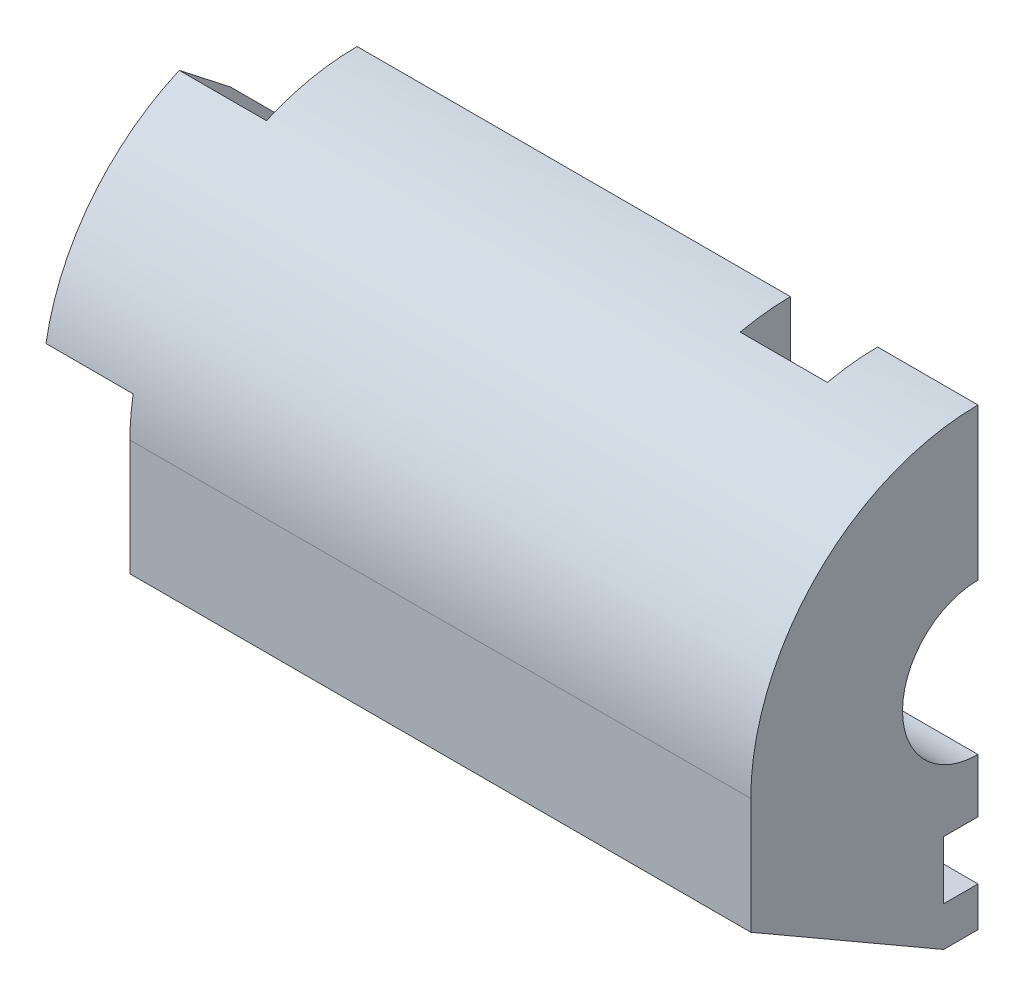
SolidWorks part; units mm, degrees
material "Alliage 1060"
ref_plane "Plan de face" through (0, 0, 0) normal (0, 0, 1) x (1, 0, 0)
ref_plane "Plan de dessus" through (0, 0, 0) normal (0, 1, 0) x (1, 0, 0)
ref_plane "Plan de droite" through (0, 0, 0) normal (1, 0, 0) x (0, 0, -1)
sketch "Esquisse1" plane through (0, 0, 0) normal (1, 0, 0) x (0, 0, -1)
  line L0 (0, 0) -> (0, 86)
  line L1 (0, 55) -> (0, -55) construction
  line L5 (-13, -86) -> (0, -86)
  line L6 (0, -86) -> (0, 0)
  line L7 (-13, -86) -> (-86, -43.8534)
  line L8 (-86, -43.8534) -> (-86, 0)
  arc A0 (0, 86) -> (-86, 0) centre (0, 0) ccw
  dimension "D1" = 86
  dimension "D2" = 86
  dimension "D3" = 13
  dimension "D4" = 86
extrude "Boss.-Extru.1" add sketch "Esquisse1" along normal blind 235 contours L8 A0 L0 L6 L5 L7
sketch "Esquisse2" plane through (0, 0, 0) normal (1, 0, 0) x (0, 0, -1)
  circle A0 centre (0, 0) radius 28.575
extrude "Enlèv. mat.-Extru.1" cut sketch "Esquisse2" along normal blind 235
sketch "Esquisse3" plane through (0, 0, 0) normal (1, 0, 0) x (0, 0, -1)
  circle A0 centre (0, 0) radius 44.45
extrude "Enlèv. mat.-Extru.2" cut sketch "Esquisse3" along normal blind 78
sketch "Esquisse4" plane through (0, 0, 0) normal (0, 0, 1) x (1, 0, 0)
  line L0 (235, 86) -> (197, 86)
  line L2 (235, 86) -> (0, 86) construction
  line L3 (197, 86) -> (197, 24.3686)
  line L4 (197, 86) -> (164, 86)
  line L5 (164, 86) -> (164, 24.3686)
  line L6 (197, 24.3686) -> (164, 24.3686)
  dimension "D1" = 38
  dimension "D2" = 33
extrude "Enlèv. mat.-Extru.3" cut sketch "Esquisse4" along normal blind 19 contours L6 L3 L4 L5
sketch "Esquisse5" plane through (0, 0, 0) normal (0, 0, 1) x (1, 0, 0)
  line L0 (235, -86) -> (235, -71)
  line L1 (235, -86) -> (235, -28.575) construction
  line L2 (235, -71) -> (125, -71)
  line L3 (235, -49) -> (235, -71)
  line L4 (125, -49) -> (235, -49)
  arc A0 (125, -71) -> (125, -49) centre (125, -60) cw
  dimension "D1" = 15
  dimension "D2" = 110
  dimension "D4" = 22
extrude "Enlèv. mat.-Extru.4" cut sketch "Esquisse5" along normal blind 13 contours A0 L2 L3 L4
sketch "Esquisse6" plane through (0, 0, 0) normal (1, 0, 0) x (0, 0, -1)
  line L0 (0, 0) -> (-40.1885, 31.3987)
  line L1 (47.3, 0) -> (-47.3, 0) construction
  line L2 (-40.1885, 31.3987) -> (-65.4307, -0.9097)
  line L3 (-14.9464, 63.7072) -> (-40.1885, 31.3987)
  line L4 (-14.9464, 63.7072) -> (-34.3296, 78.851)
  line L5 (-65.4307, -0.9097) -> (-84.8139, 14.2341)
  line L7 (-34.3296, 78.851) -> (-14.9464, 63.7072)
  line L8 (-14.9464, 63.7072) -> (-65.4307, -0.9097)
  line L9 (-65.4307, -0.9097) -> (-84.7673, 14.5089)
  arc A0 (0, 86) -> (-86, 0) centre (0, 0) ccw construction
  arc A1 (-84.8139, 14.2341) -> (-34.3296, 78.851) centre (0, 0) cw
  dimension "D1" = 38
extrude "Boss.-Extru.2" add sketch "Esquisse6" against normal blind 33 contours A1 L9 L2 L3 L4
equation "\"A\"= 235"
equation "\"B\"= 110"
equation "\"C\"= 86"
equation "\"D2@Esquisse1\"=\"C\""
equation "\"D1@Esquisse1\"=\"C\""
equation "\"D4@Esquisse1\"=\"C\""
equation "\"D1@Boss.-Extru.1\"=\"A\""
equation "\"D2@Esquisse5\"=\"B\""
